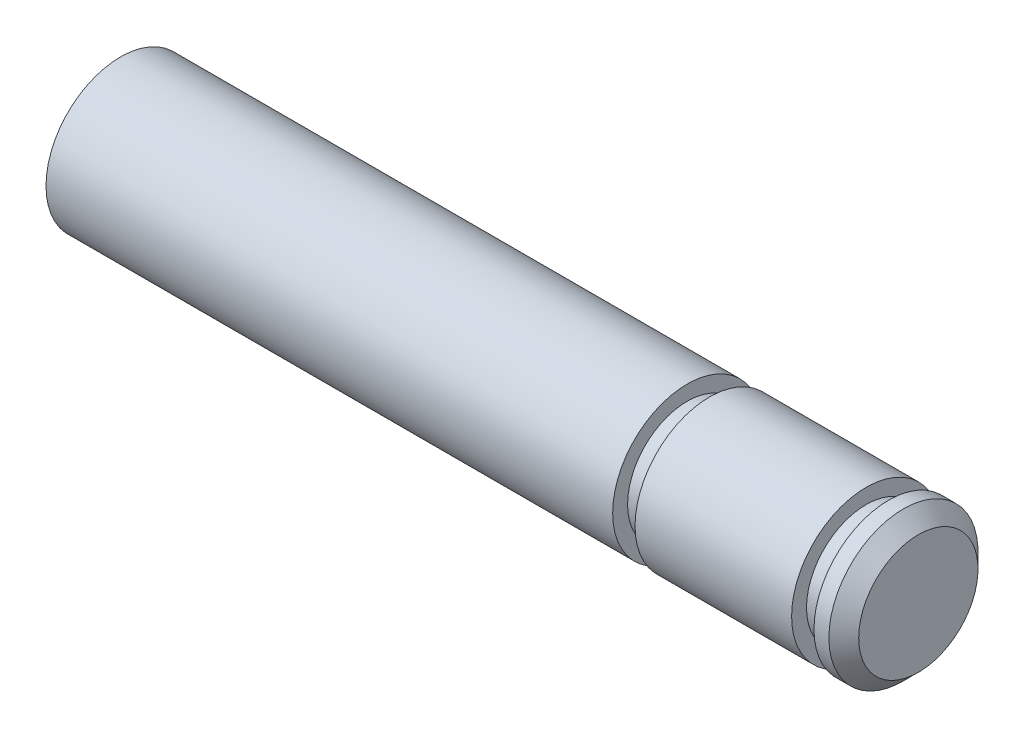
SolidWorks part; units mm, degrees
ref_plane "Front Plane" through (0, 0, 0) normal (0, 0, 1) x (1, 0, 0)
ref_plane "Top Plane" through (0, 0, 0) normal (0, 1, 0) x (1, 0, 0)
ref_plane "Right Plane" through (0, 0, 0) normal (1, 0, 0) x (0, 0, -1)
sketch "Sketch1" plane through (0, 0, 0) normal (0, 0, 1) x (1, 0, 0)
  line L0 (0, 0) -> (0, 5)
  line L1 (0, 5) -> (38, 5)
  line L2 (50, 5) -> (50, 4)
  line L3 (50, 4) -> (51.5, 4)
  line L4 (51.5, 4) -> (51.5, 5)
  line L5 (51.5, 5) -> (53.5, 5)
  line L6 (53.5, 5) -> (53.5, 0)
  line L7 (53.5, 0) -> (0, 0)
  line L8 (38, 5) -> (38, 4)
  line L9 (-16.6781, 0) -> (0, 0) construction
  line L10 (38, 4) -> (39.5, 4)
  line L11 (39.5, 4) -> (39.5, 5)
  line L12 (39.5, 5) -> (50, 5)
  dimension "D1" = 8
  dimension "D2" = 10
  dimension "D3" = 1.5
  dimension "D4" = 2
  dimension "D5" = 50
  dimension "D6" = 10.5
revolve "Revolve1" add sketch "Sketch1" angle 360 about L9
chamfer "Chamfer1" distance 1 angle 45 1 edges at (53.5, 0, 5)
